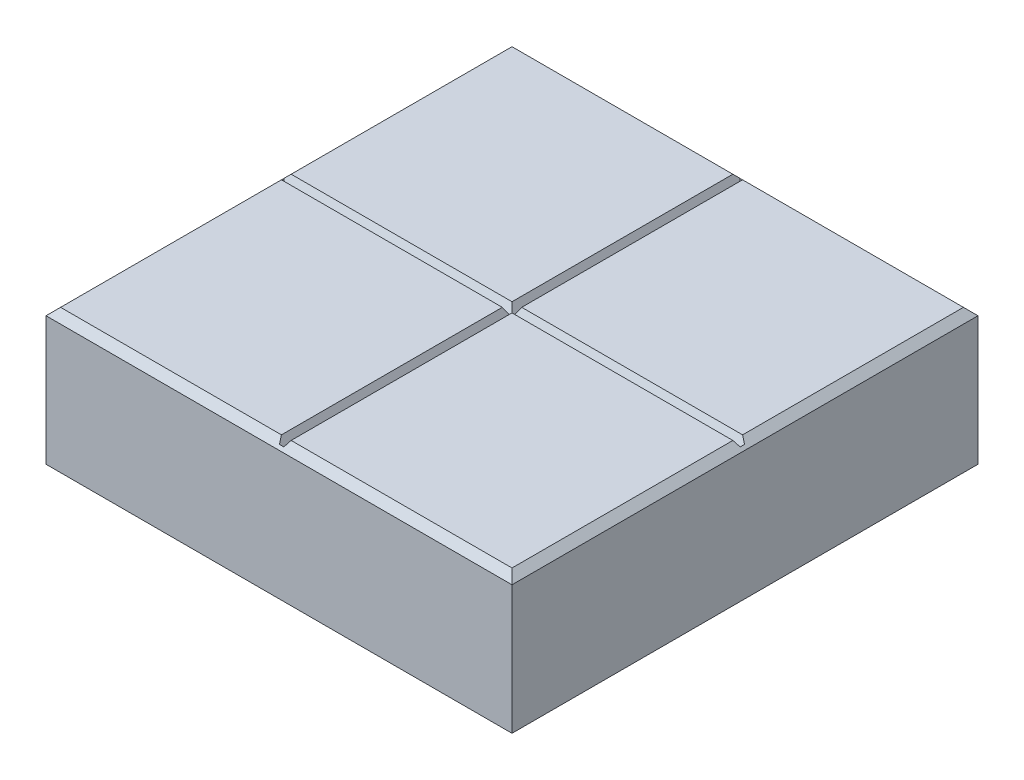
SolidWorks part; units mm, degrees
ref_plane "Front Plane" through (0, 0, 0) normal (0, 0, 1) x (1, 0, 0)
ref_plane "Top Plane" through (0, 0, 0) normal (0, 1, 0) x (1, 0, 0)
ref_plane "Right Plane" through (0, 0, 0) normal (1, 0, 0) x (0, 0, -1)
sketch "Sketch1" plane through (0, 0, 0) normal (0, 1, 0) x (1, 0, 0)
  line L1 (-120, -120) -> (120, -120)
  line L2 (-120, -120) -> (-120, 120)
  line L3 (-120, 120) -> (120, 120)
  line L4 (120, -120) -> (120, 120)
  line L5 (-120, -120) -> (120, 120) construction
  line L6 (-120, 120) -> (120, -120) construction
  point P0 (0, 0)
extrude "Boss-Extrude1" add sketch "Sketch1" along normal blind 70
sketch "Sketch2" plane through (0, 70, 0) normal (0, 1, 0) x (1, 0, 0)
  line L0 (120, 120) -> (-120, 120) construction
  line L1 (2.5, -120) -> (-2.5, -120)
  line L2 (2.5, -120) -> (2.5, 120)
  line L3 (2.5, 120) -> (-2.5, 120)
  line L4 (-2.5, -120) -> (-2.5, 120)
  line L5 (2.5, -120) -> (-2.5, 120) construction
  line L6 (2.5, 120) -> (-2.5, -120) construction
  line L7 (120, -120) -> (120, 120) construction
  line L8 (-120, -2.5) -> (120, -2.5)
  line L9 (-120, -2.5) -> (-120, 2.5)
  line L10 (-120, 2.5) -> (120, 2.5)
  line L11 (120, -2.5) -> (120, 2.5)
  line L12 (-120, -2.5) -> (120, 2.5) construction
  line L13 (-120, 2.5) -> (120, -2.5) construction
  point P0 (0, 0)
  point P8 (0, 0)
  line M2 (120, -120) -> (120, 120)
  line M3 (120, 120) -> (-120, 120)
  line M4 (-120, 120) -> (-120, -120)
  line M5 (-120, -120) -> (120, -120)
extrude "Cut-Extrude1" cut sketch "Sketch2" against normal blind 5 draft 30 contours L4 L10 L2 M3 | L10 L8 L4 M4 | L10 L4 L8 L2 | L8 L4 L2 M5 | L10 L2 L8 M2
sketch "Sketch3" plane through (0, 0, 0) normal (0, 0, 1) x (1, 0, 0)
  line L0 (0, 0) -> (0, 70) construction
  line L1 (-2.5, 70) -> (2.5, 70) construction
sketch "Sketch4" plane through (0, 70, 0) normal (0, 1, 0) x (1, 0, 0)
  line L0 (-120, 2.5) -> (-120, -2.5) construction
  line L1 (-116.25, -130) -> (-123.75, -130)
  line L2 (-116.25, -130) -> (-116.25, 130)
  line L3 (-116.25, 130) -> (-123.75, 130)
  line L4 (-123.75, -130) -> (-123.75, 130)
  line L5 (-116.25, -130) -> (-123.75, 130) construction
  line L6 (-116.25, 130) -> (-123.75, -130) construction
  point P0 (-120, 0)
  dimension "D1" = 7.5
  dimension "D2" = 260
extrude "Cut-Extrude2" cut sketch "Sketch4" against normal blind 10 draft 45
pattern_circular "CirPattern1" count 4 over 360 about axis through (0, 0, 0) along (0, 1, 0) of "Cut-Extrude2"
